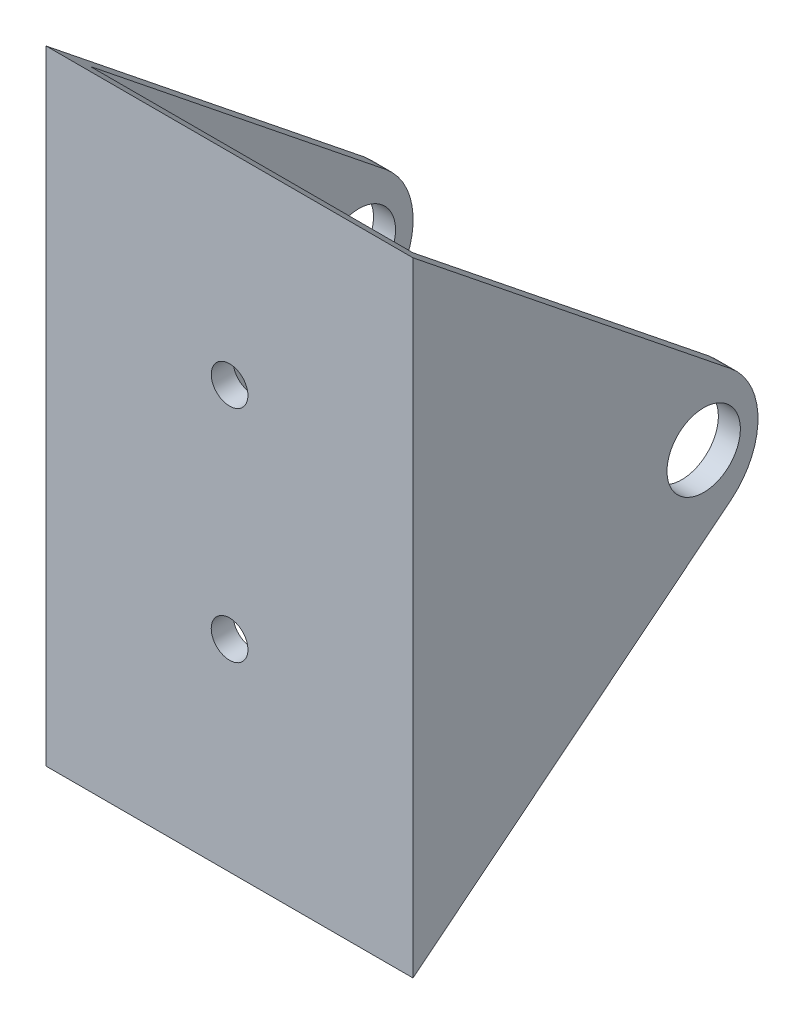
SolidWorks part; units mm, degrees
ref_plane "Front Plane" through (0, 0, 0) normal (0, 0, 1) x (1, 0, 0)
ref_plane "Top Plane" through (0, 0, 0) normal (0, 1, 0) x (1, 0, 0)
ref_plane "Right Plane" through (0, 0, 0) normal (1, 0, 0) x (0, 0, -1)
sketch "Sketch1" plane through (0, 0, 0) normal (0, 0, 1) x (1, 0, 0)
  line L1 (-25, 42.5) -> (25, 42.5)
  line L2 (-25, 42.5) -> (-25, -42.5)
  line L3 (-25, -42.5) -> (25, -42.5)
  line L4 (25, 42.5) -> (25, -42.5)
  line L5 (-25, 42.5) -> (25, -42.5) construction
  line L6 (-25, -42.5) -> (25, 42.5) construction
  point P0 (0, 0)
  dimension "D1" = 85
  dimension "D2" = 50
extrude "Boss-Extrude1" add sketch "Sketch1" along normal blind 3
sketch "Sketch4" plane through (0, 0, 0) normal (0, 0, -1) x (-1, 0, 0)
  line L0 (-25, 42.5) -> (-25, -42.5)
  line L1 (-25, -42.5) -> (-22, -42.5)
  line L2 (25, -42.5) -> (-25, -42.5) construction
  line L3 (-22, -42.5) -> (-22, 42.5)
  line L4 (-25, 42.5) -> (25, 42.5) construction
  line L5 (-22, 42.5) -> (-25, 42.5)
  line L6 (25, 42.5) -> (22, 42.5)
  line L7 (22, 42.5) -> (22, -42.5)
  line L8 (22, -42.5) -> (25, -42.5)
  line L9 (25, -42.5) -> (25, 42.5)
  dimension "D1" = 3
  dimension "D2" = 3
extrude "Boss-Extrude2" add sketch "Sketch4" along normal blind 50
sketch "Sketch5" plane through (25, 0, 0) normal (1, 0, 0) x (0, 0, -1)
  line L0 (-3, -42.5) -> (50, 0)
  line L1 (50, 42.5) -> (50, -42.5) construction
  line L2 (50, 0) -> (-3, 42.5)
  line L3 (-3, -42.5) -> (50, -42.5)
  line L4 (50, -42.5) -> (50, 0)
  line L5 (50, 42.5) -> (-3, 42.5)
  line L6 (50, 0) -> (50, 42.5)
  line M1 (-3, -42.5) -> (50, -42.5)
  line M2 (50, -42.5) -> (50, 42.5)
  line M3 (50, 42.5) -> (-3, 42.5)
extrude "Cut-Extrude1" cut sketch "Sketch5" against normal blind 50 contours L0 M1 M2 | L2 M2 M3
fillet "Fillet2" radius 10 2 edges at (-23.5, 0, -50) (23.5, 0, -50)
sketch "Sketch6" plane through (25, 0, 0) normal (1, 0, 0) x (0, 0, -1)
  line L0 (-3, 0) -> (44.0151, 0) construction
  line L1 (-3, -42.5) -> (-3, 42.5) construction
  arc A0 (40.2711, -7.8015) -> (40.2711, 7.8015) centre (34.0151, 0) ccw construction
  circle A1 centre (36.6148, 0) radius 5
  point P9 (36.6148, 0)
  dimension "D1" = 10
extrude "Cut-Extrude2" cut sketch "Sketch6" against normal blind 50
sketch "Sketch7" plane through (0, 0, 3) normal (0, 0, 1) x (1, 0, 0)
  line L0 (0, 42.5) -> (0, -42.5) construction
  line L1 (25, 42.5) -> (-25, 42.5) construction
  line L2 (-25, -42.5) -> (25, -42.5) construction
  line L3 (-25, 0) -> (25, 0) construction
  line L4 (-25, 42.5) -> (-25, -42.5) construction
  line L5 (25, -42.5) -> (25, 42.5) construction
  circle A0 centre (0, 15) radius 2.5
  circle A1 centre (0, -15) radius 2.5
  dimension "D1" = 5
  dimension "D2" = 15
extrude "Cut-Extrude3" cut sketch "Sketch7" against normal blind 20
